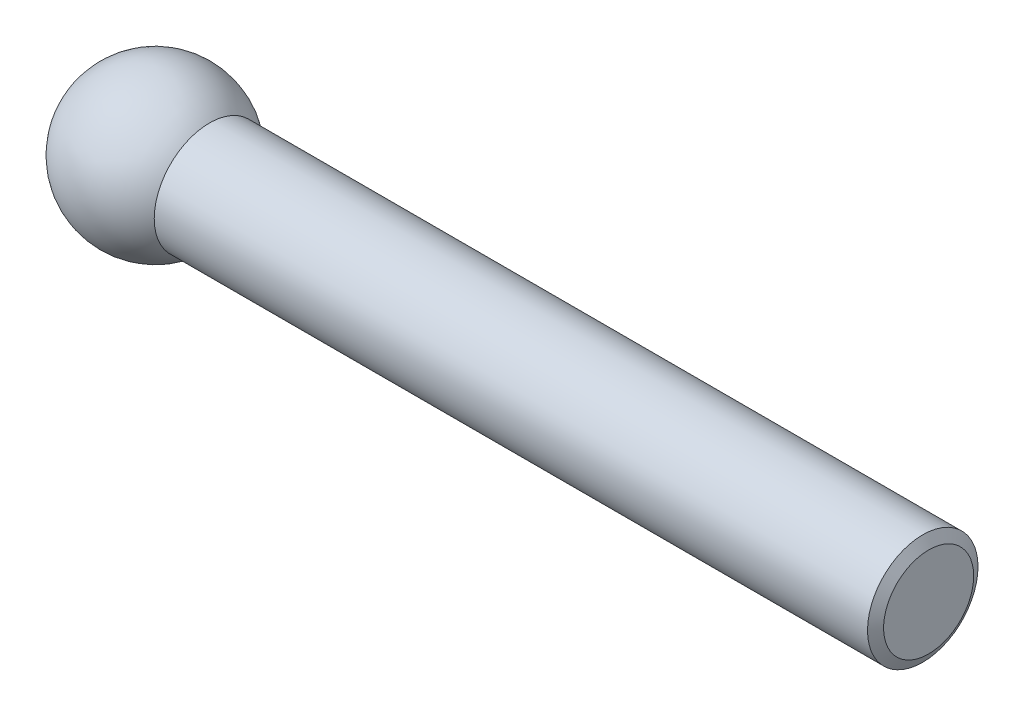
SolidWorks part; units mm, degrees
ref_plane "Front Plane" through (0, 0, 0) normal (0, 0, 1) x (1, 0, 0)
ref_plane "Top Plane" through (0, 0, 0) normal (0, 1, 0) x (1, 0, 0)
ref_plane "Right Plane" through (0, 0, 0) normal (1, 0, 0) x (0, 0, -1)
sketch "Sketch1" plane through (0, 0, 0) normal (1, 0, 0) x (0, 0, -1)
  circle A0 centre (0, 0) radius 14.2875
  dimension "D1" = 28.575
extrude "Boss-Extrude1" add sketch "Sketch1" along normal blind 200
ref_plane "Plane1" through (201.016, 0, 0) normal (1, 0, 0) x (0, 0, -1)
chamfer "Chamfer1" distance 1.524 angle 60 1 edges at (200, 0, -14.2875)
sketch "Sketch4" plane through (0, 0, 0) normal (0, 0, 1) x (1, 0, 0)
  line L0 (0, 14.2875) -> (0, -14.2875) construction
  line L1 (-20, 0) -> (20, 0)
  line L2 (0, 0) -> (46.2038, 0) construction
  arc A0 (20, 0) -> (-20, 0) centre (0, 0) ccw
  dimension "D1" = 40
revolve "Revolve1" add sketch "Sketch4" angle 360 about L2
ref_plane "Plane2" through (81, 0, 0) normal (1, 0, 0) x (0, 0, -1)
sketch "Sketch5" plane through (81, 0, 0) normal (1, 0, 0) x (0, 0, -1)
  circle A0 centre (0, 0) radius 14.2875 construction
  circle A1 centre (0, 0) radius 14.2875
